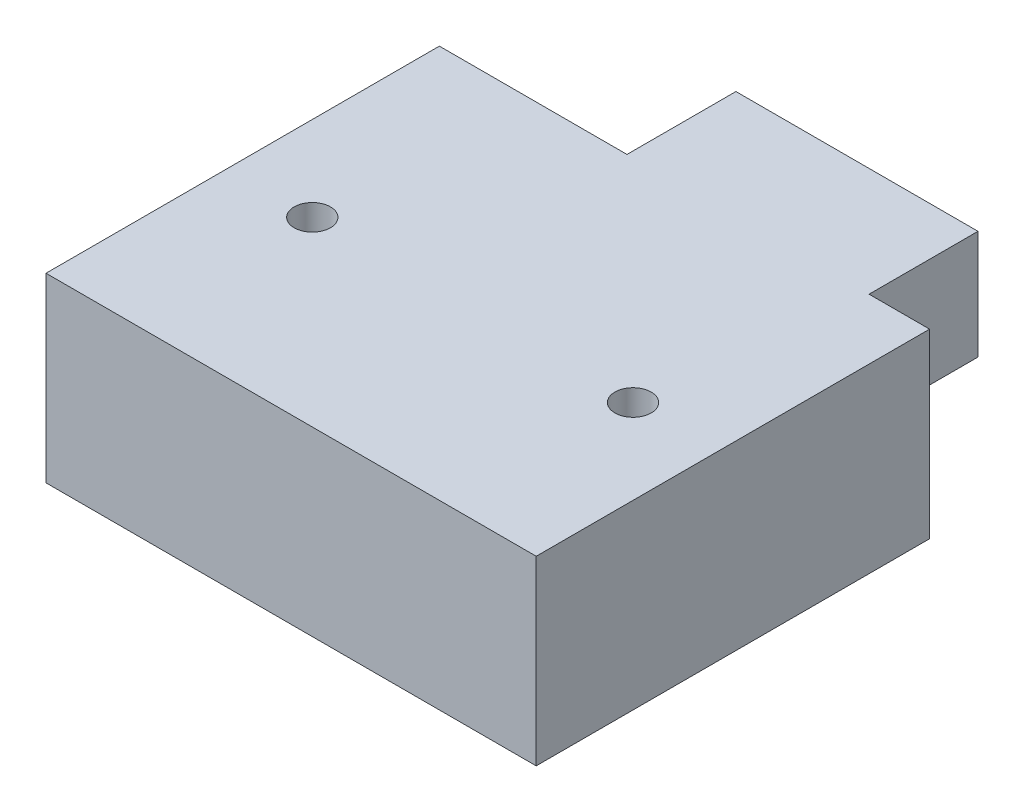
SolidWorks part; units mm, degrees
ref_plane "Front Plane" through (0, 0, 0) normal (0, 0, 1) x (1, 0, 0)
ref_plane "Top Plane" through (0, 0, 0) normal (0, 1, 0) x (1, 0, 0)
ref_plane "Right Plane" through (0, 0, 0) normal (1, 0, 0) x (0, 0, -1)
sketch "Sketch1" plane through (0, 0, 0) normal (0, 1, 0) x (1, 0, 0)
  line L1 (-20.25, -16.25) -> (20.25, -16.25)
  line L2 (-20.25, -16.25) -> (-20.25, 16.25)
  line L3 (-20.25, 16.25) -> (20.25, 16.25)
  line L4 (20.25, -16.25) -> (20.25, 16.25)
  line L5 (-20.25, -16.25) -> (20.25, 16.25) construction
  line L6 (-20.25, 16.25) -> (20.25, -16.25) construction
  circle A0 centre (-13.25, -1.25) radius 1.5
  circle A1 centre (13.25, -1.25) radius 1.5
  point P0 (0, 0)
  dimension "D3" = 3
  dimension "D6" = 3
  dimension "D1" = 40.5
  dimension "D2" = 32.5
  dimension "D4" = 7
  dimension "D5" = 7
  dimension "D7" = 17.5
  dimension "D8" = 17.5
extrude "Boss-Extrude1" add sketch "Sketch1" along normal blind 15
sketch "Sketch3" plane through (0, 0, -16.25) normal (0, 0, -1) x (-1, 0, 0)
  line L0 (-20.25, 15) -> (20.25, 15) construction
  line L1 (-15.25, 15) -> (4.75, 15)
  line L2 (-15.25, 15) -> (-15.25, 6)
  line L3 (-15.25, 6) -> (4.75, 6)
  line L4 (4.75, 15) -> (4.75, 6)
  line L6 (-20.25, 15) -> (-20.25, 0) construction
  dimension "D1" = 20
  dimension "D2" = 9
  dimension "D3" = 5
extrude "Boss-Extrude2" add sketch "Sketch3" along normal blind 9
